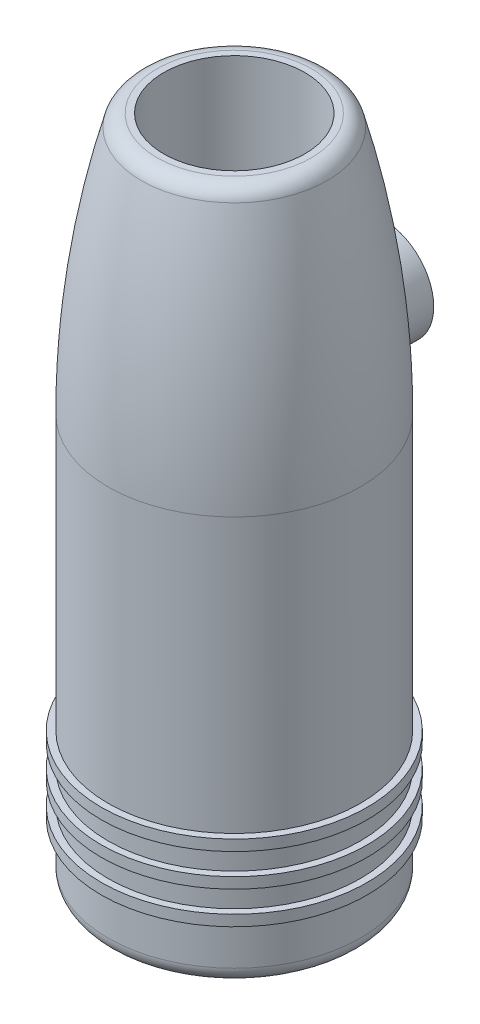
SolidWorks part; units mm, degrees
ref_plane "Plan de face" through (0, 0, 0) normal (0, 0, 1) x (1, 0, 0)
ref_plane "Plan de dessus" through (0, 0, 0) normal (0, 1, 0) x (1, 0, 0)
ref_plane "Plan de droite" through (0, 0, 0) normal (1, 0, 0) x (0, 0, -1)
sketch "Esquisse1" plane through (0, 0, 0) normal (0, 0, 1) x (1, 0, 0)
  line L0 (0, 0) -> (0, 77.8772) construction
  line L1 (23.25, 0) -> (23.25, 10.5)
  line L2 (23.25, 10.5) -> (24.5, 10.5)
  line L3 (24.5, 10.5) -> (24.5, 12.5)
  line L4 (24.5, 12.5) -> (23.25, 12.5)
  line L5 (23.25, 12.5) -> (23.25, 16.5)
  line L6 (23.25, 16.5) -> (24.5, 16.5)
  line L7 (24.5, 16.5) -> (24.5, 18.5)
  line L8 (24.5, 18.5) -> (23.25, 18.5)
  line L9 (23.25, 18.5) -> (23.25, 22.5)
  line L10 (23.25, 22.5) -> (24.5, 22.5)
  line L11 (24.5, 22.5) -> (24.5, 24.5)
  line L12 (24.5, 24.5) -> (23.25, 24.5)
  line L13 (23.25, 24.5) -> (23.25, 75)
  line L15 (16.5, 123) -> (13, 123)
  line L16 (23.25, 0) -> (19, 0)
  line L17 (19, 0) -> (19, 50)
  line L18 (19, 50) -> (13, 50)
  line L20 (13, 50) -> (13, 123)
  arc A0 (23.25, 75) -> (16.5, 123) centre (-150.7917, 75) ccw
  dimension "D1" = 123
  dimension "D2" = 38
  dimension "D3" = 46.5
  dimension "D4" = 49
  dimension "D5" = 24.5
  dimension "D6" = 2
  dimension "D7" = 4
  dimension "D8" = 2
  dimension "D9" = 4
  dimension "D10" = 2
  dimension "D11" = 26
  dimension "D12" = 75
  dimension "D13" = 33
  dimension "D14" = 50
revolve "Révolution1" add sketch "Esquisse1" angle 360 about L0
sketch "Esquisse2" plane through (0, 0, 0) normal (0, 0, 1) x (1, 0, 0)
  circle A0 centre (0, 33) radius 2.5
  dimension "D1" = 5
  dimension "D2" = 33
extrude "Enlèv. mat.-Extru.1" cut sketch "Esquisse2" against normal through all
ref_plane "Plan1" through (0, 0, -27.5) normal (0, 0, 1) x (1, 0, 0)
sketch "Esquisse3" plane through (0, 0, -27.5) normal (0, 0, 1) x (1, 0, 0)
  line L0 (0, 75) -> (0, 24.5) construction
  circle A0 centre (0, 83) radius 9.25
  circle A1 centre (0, 33) radius 2.5 construction
  dimension "D1" = 18.5
  dimension "D2" = 50
extrude "Boss.-Extru.1" add sketch "Esquisse3" along normal up to next
fillet "Congé1" radius 1 2 edges at (-1.0976, 73.8154, -23.2241) (0.5792, 92.2318, -22.3873)
hole_wizard "Trou taraudé M81" positions "Esquisse5" profile "Esquisse4" tap size "M8" standard "ISO"
sketch "Esquisse5" plane through (0, 0, -27.5) normal (0, 0, -1) x (-1, 0, 0)
  point P0 (0, 83)
sketch "Esquisse4" plane through (0, 83, -27.5) normal (1, 0, 0) x (0, 1, 0)
  line L0 (0, 0) -> (0, 24.2929)
  line L1 (0, 24.2929) -> (3.4, 22.25)
  line L2 (3.4, 22.25) -> (3.4, 0)
  line L5 (3.4, 0) -> (0, 0)
  line L10 (0, 24.2929) -> (-3.4, 22.25) construction
  line L11 (0, -6.35) -> (0, 107.95) construction
  dimension "Diamètre du trou pour taraudage" = 6.8
  dimension "Profondeur du trou pour taraudage" = 22.25
  dimension "Angle de pointe" = 118
cosmetic thread "Filetage de perçage1" parameters "D1"=14.9525, "D2"=8
fillet "Congé2" radius 3 1 edges at (0, 0, -23.25)
fillet "Congé3" radius 3 1 edges at (0, 123, -16.5)
ref_plane "Plan2" through (0, 0, -23.15) normal (0, 0, 1) x (1, 0, 0)
sketch "Esquisse6" plane through (0, 0, -23.15) normal (0, 0, 1) x (1, 0, 0)
  circle A0 centre (0, 33) radius 3.85
  circle A1 centre (0, 33) radius 3.85 construction
extrude "Enlèv. mat.-Extru.2" cut sketch "Esquisse6" against normal through all
